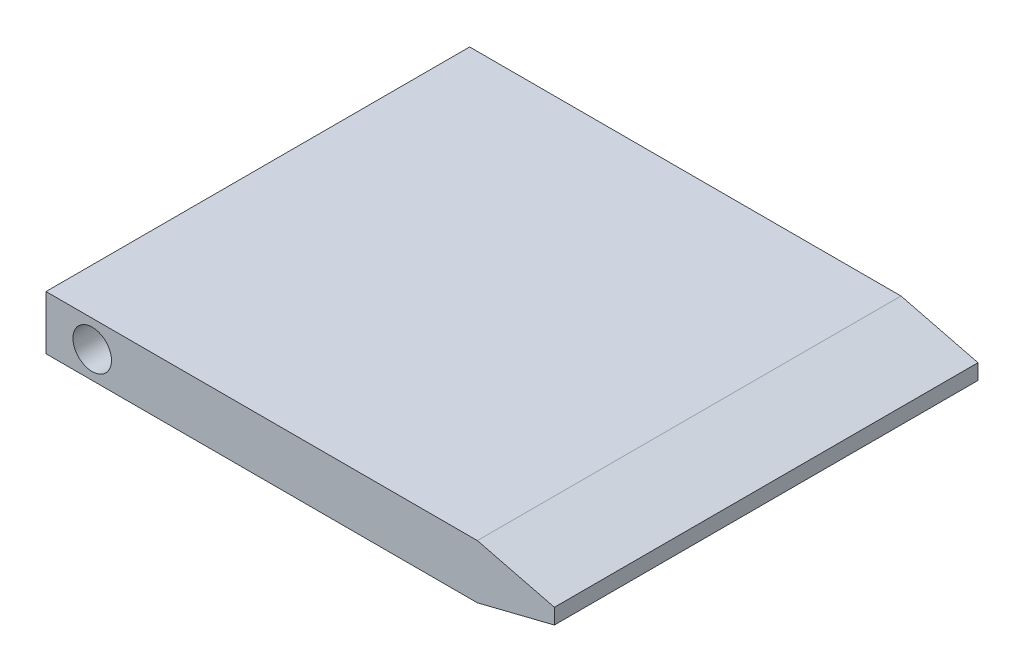
SolidWorks part; units mm, degrees
ref_plane "Front Plane" through (0, 0, 0) normal (0, 0, 1) x (1, 0, 0)
ref_plane "Top Plane" through (0, 0, 0) normal (0, 1, 0) x (1, 0, 0)
ref_plane "Right Plane" through (0, 0, 0) normal (1, 0, 0) x (0, 0, -1)
sketch "Sketch1" plane through (0, 0, 0) normal (0, 1, 0) x (1, 0, 0)
  line L1 (-23.5938, -8.75) -> (20.4062, -8.75)
  line L2 (-23.5938, -8.75) -> (-23.5938, 46.25)
  line L3 (-23.5938, 46.25) -> (20.4062, 46.25)
  line L4 (20.4062, -8.75) -> (20.4062, 46.25)
  dimension "D1" = 55
  dimension "D2" = 44
extrude "Boss-Extrude1" add sketch "Sketch1" along normal blind 7
sketch "Sketch2" plane through (0, 0, 8.75) normal (0, 0, 1) x (1, 0, 0)
  line L0 (-23.5938, 7) -> (-17.5938, 7)
  line L1 (-23.5938, 7) -> (20.4062, 7) construction
  line L2 (-17.5938, 7) -> (-17.5938, 0)
  line L3 (-23.5938, 0) -> (20.4062, 0) construction
  circle A0 centre (-17.5938, 3.5) radius 2.5
  dimension "D2" = 5
  dimension "D1" = 6
extrude "Cut-Extrude1" cut sketch "Sketch2" against normal blind 100 contours L2 A0 | L2 A0
sketch "Sketch3" plane through (20.4062, 0, 0) normal (1, 0, 0) x (0, 0, -1)
  line L1 (-8.75, 7) -> (46.25, 7)
  line L2 (-8.75, 7) -> (-8.75, 0)
  line L3 (-8.75, 0) -> (46.25, 0)
  line L4 (46.25, 7) -> (46.25, 0)
extrude "Boss-Extrude2" add sketch "Sketch3" along normal blind 22
chamfer "Chamfer1" distance 10 distance2 2.5 2 edges at (42.4062, 7, -18.75) (42.4062, 0, -18.75)
